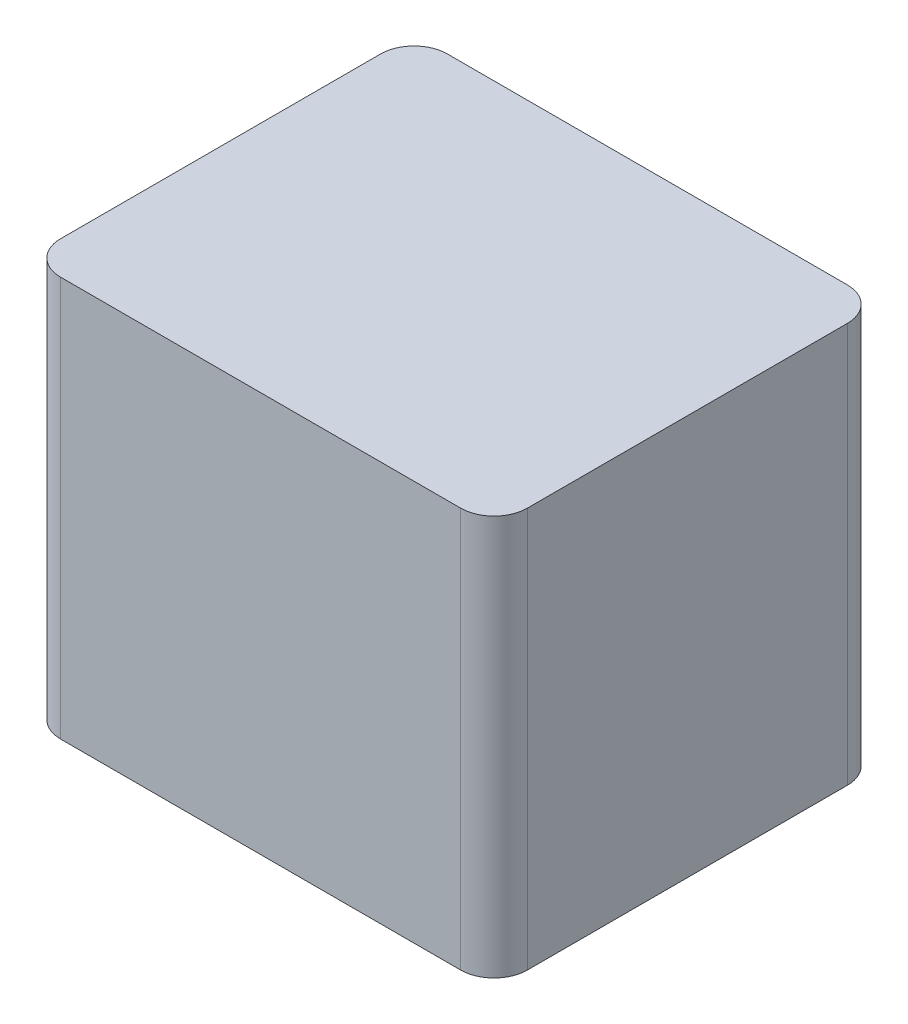
SolidWorks part; units mm, degrees
ref_plane "Front Plane" through (0, 0, 0) normal (0, 0, 1) x (1, 0, 0)
ref_plane "Top Plane" through (0, 0, 0) normal (0, 1, 0) x (1, 0, 0)
ref_plane "Right Plane" through (0, 0, 0) normal (1, 0, 0) x (0, 0, -1)
sketch "Sketch1" plane through (0, 0, 0) normal (0, 1, 0) x (1, 0, 0)
  line L1 (-30, -29) -> (30, -29)
  line L2 (-35, -24) -> (-35, 24)
  line L3 (-30, 29) -> (30, 29)
  line L4 (35, -24) -> (35, 24)
  line L5 (-35, -29) -> (35, 29) construction
  line L6 (-35, 29) -> (35, -29) construction
  arc A0 (-30, -29) -> (-35, -24) centre (-30, -24) cw
  arc A1 (30, -29) -> (35, -24) centre (30, -24) ccw
  arc A2 (30, 29) -> (35, 24) centre (30, 24) cw
  arc A3 (-35, 24) -> (-30, 29) centre (-30, 24) cw
  point P0 (0, 0)
  dimension "D3" = 5
  dimension "D1" = 70
  dimension "D2" = 58
extrude "Boss-Extrude1" add sketch "Sketch1" along normal mid plane 60
